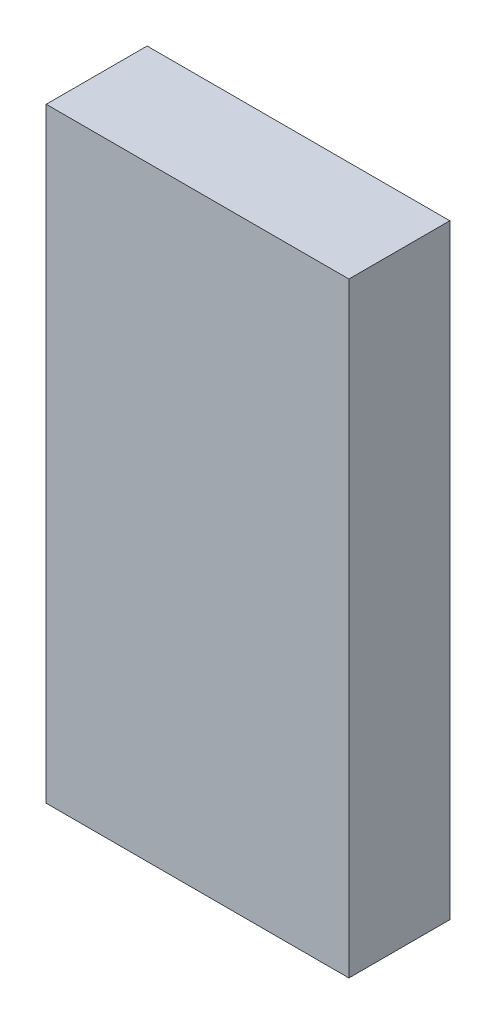
SolidWorks part; units mm, degrees
ref_plane "Front Plane" through (0, 0, 0) normal (0, 0, 1) x (1, 0, 0)
ref_plane "Top Plane" through (0, 0, 0) normal (0, 1, 0) x (1, 0, 0)
ref_plane "Right Plane" through (0, 0, 0) normal (1, 0, 0) x (0, 0, -1)
sketch "Sketch1" plane through (0, 0, 0) normal (0, 0, 1) x (1, 0, 0)
  line L1 (-3, 6) -> (3, 6)
  line L2 (-3, 6) -> (-3, -6)
  line L3 (-3, -6) -> (3, -6)
  line L4 (3, 6) -> (3, -6)
  line L5 (-3, 6) -> (3, -6) construction
  line L6 (-3, -6) -> (3, 6) construction
  point P0 (0, 0)
  dimension "D1" = 6
  dimension "D2" = 12
extrude "Boss-Extrude1" add sketch "Sketch1" along normal blind 2
